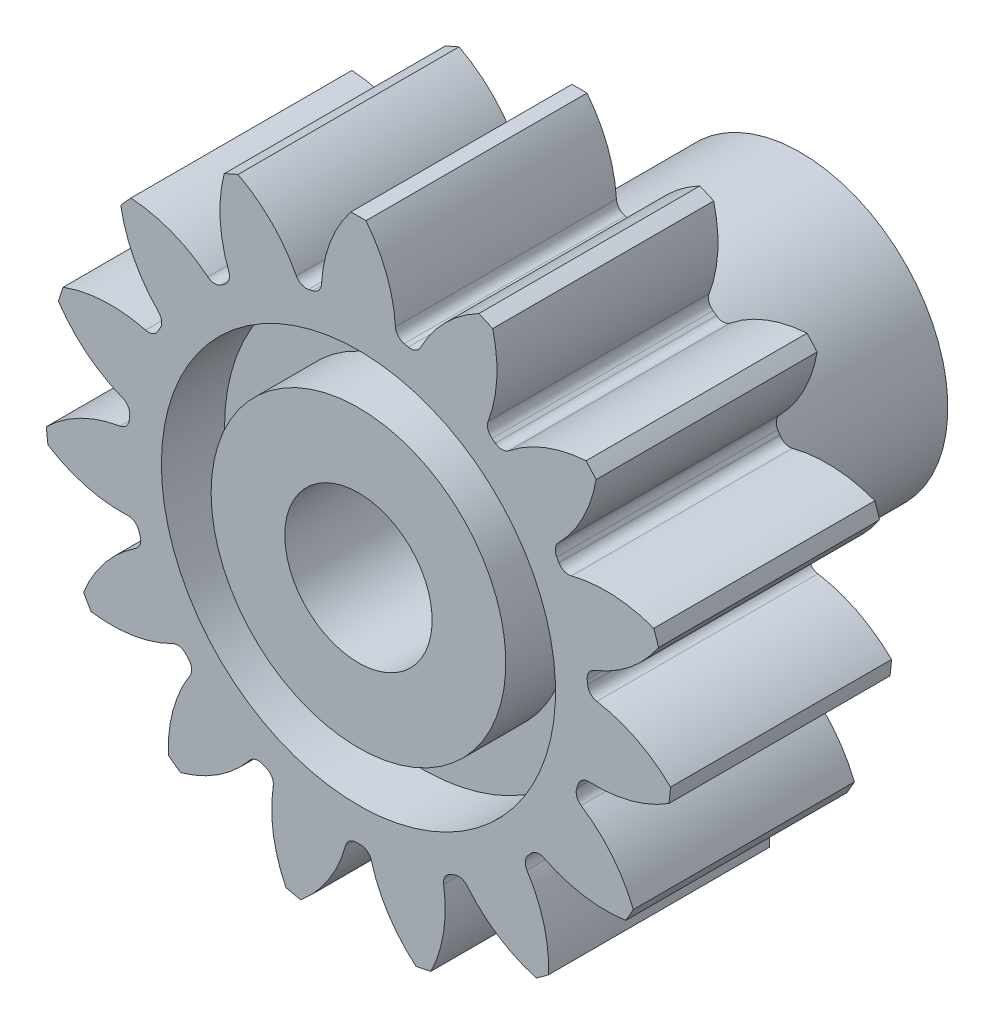
SolidWorks part; units mm, degrees
ref_plane "Front Plane" through (0, 0, 0) normal (0, 0, 1) x (1, 0, 0)
ref_plane "Top Plane" through (0, 0, 0) normal (0, 1, 0) x (1, 0, 0)
ref_plane "Right Plane" through (0, 0, 0) normal (1, 0, 0) x (0, 0, -1)
sketch "Sketch1" plane through (0, 0, 0) normal (1, 0, 0) x (0, 0, -1)
  line L0 (-6, 0) -> (-6, 8.5)
  line L1 (-6, 8.5) -> (0, 8.5)
  line L2 (0, 8.5) -> (0, 4)
  line L3 (0, 4) -> (6, 4)
  line L4 (6, 4) -> (6, 0)
  line L5 (6, 0) -> (-6, 0) construction
  line L6 (-6, 2) -> (6, 2)
  point P9 (-6, 5.35)
  dimension "OD" = 17
  dimension "Face Width" = 6
  dimension "Hub Width" = 6
  dimension "Hub Diameter" = 8
  dimension "For Shaft Diameter" = 4
  dimension "Overall Width" = 12
  dimension "Under Cut Diameter" = 10.7
sketch "Sketch2" plane through (0, 0, 0) normal (0, 0, 1) x (1, 0, 0)
  line L0 (-1.273, 6.119) -> (-0.4064, 8.5)
  line L1 (-0.4064, 8.5) -> (0.4064, 8.5)
  line L2 (0.4064, 8.5) -> (1.273, 6.119)
  line L3 (0, 8.5) -> (0, 0) construction
  line L4 (0, 0) -> (-1.7672, 8.3143) construction
  line L5 (0, 0) -> (1.7672, 8.3143) construction
  line L6 (-3.6518, 5.0722) -> (-3.8285, 7.5998)
  line L7 (-3.8285, 7.5998) -> (-3.086, 7.9304)
  line L8 (-3.086, 7.9304) -> (-1.3258, 6.1078)
  line L9 (-3.4573, 7.7651) -> (0, 0) construction
  line L11 (-0.4064, 8.5) -> (0, 8.5) construction
  line L12 (-0.7854, 7.4588) -> (0.7854, 7.4588) construction
  circle A0 centre (0, 0) radius 7.5 construction
  circle A2 centre (0, 0) radius 8.5
  circle A3 centre (0, 0) radius 6.25
  arc A5 (-0.2032, 8.5) -> (-1.0101, 6.1678) centre (2.7162, 6.1843) ccw
  arc A6 (1.0101, 6.1678) -> (0.2032, 8.5) centre (-2.7162, 6.1843) ccw
  arc A7 (-1.5859, 6.0454) -> (-3.2716, 7.8478) centre (-4.9967, 4.5449) ccw
  arc A8 (-0.7854, 7.4588) -> (0.7854, 7.4588) centre (0, 0) cw
  point P3 (0, 7.5)
  point P5 (3.0505, 6.8516)
  point P9 (5.5736, 5.0185)
  point P10 (7.1329, 2.3176)
  point P11 (7.4589, -0.784)
  point P12 (6.4952, -3.75)
  point P13 (4.4084, -6.0676)
  point P14 (1.5593, -7.3361)
  point P15 (-1.5593, -7.3361)
  point P16 (-4.4084, -6.0676)
  point P17 (-6.4952, -3.75)
  point P18 (-7.4589, -0.784)
  point P19 (-7.1329, 2.3176)
  point P20 (-5.5736, 5.0185)
  point P21 (-3.0505, 6.8516)
  point P31 (0, 0)
  dimension "Gear Pitch Diameter" = 15
  dimension "Pressure Angle" = 20
  dimension "Addendum" = 1
  dimension "Dedendum" = 1.25
  dimension "D1" = 24
  dimension "D2" = 1.5708
  dimension "Number of Teeth" = 15
sketch "Sketch3" plane through (0, 0, 0) normal (1, 0, 0) x (0, 0, -1)
  line L0 (-6, 8.5) -> (0, 8.5) construction
  line L1 (6, 4) -> (6, 0) construction
  line L2 (0, 4) -> (6, 4) construction
  line L3 (0, 8.5) -> (0, 4) construction
  line L4 (-6, 0) -> (-6, 8.5) construction
  line L5 (-6, 2) -> (6, 2) construction
  line L6 (-6, 8.5) -> (0, 8.5)
  line L7 (6, 4) -> (6, 2)
  line L8 (-6, 4) -> (-4.2857, 4)
  line L9 (0, 8.5) -> (0, 5.35)
  line L10 (-6, 2) -> (-6, 4)
  line L11 (-6, 2) -> (6, 2)
  line L12 (-6, 5.35) -> (-4.2857, 5.35)
  line L13 (-4.2857, 5.35) -> (-4.2857, 4)
  line L14 (0, 5.35) -> (-1.7143, 5.35)
  line L15 (-1.7143, 5.35) -> (-1.7143, 4)
  line L16 (-1.7143, 4) -> (6, 4)
  line L17 (-6, 5.35) -> (-6, 8.5)
  dimension "D1" = 1.7143
revolve "Revolve1" add sketch "Sketch3" angle 360 about L5
sketch "Sketch4" plane through (0, 0, 6) normal (0, 0, 1) x (1, 0, 0)
  arc A1 (-0.2032, 8.5) -> (-1.0101, 6.1678) centre (2.7162, 6.1843) ccw construction
  arc A2 (-1.5859, 6.0454) -> (-3.2716, 7.8478) centre (-4.9967, 4.5449) ccw construction
  arc A3 (-0.2052, 8.4975) -> (-1.0038, 6.4015) centre (2.7162, 6.1843) ccw
  arc A4 (-1.6867, 6.2564) -> (-3.2688, 7.8463) centre (-4.9967, 4.5449) ccw
  circle A5 centre (0, 0) radius 8.5 construction
  arc A6 (-0.2052, 8.4975) -> (-3.2688, 7.8463) centre (0, 0) ccw
  circle A7 centre (0, 0) radius 6.25 construction
  arc A8 (-1.2436, 6.125) -> (-1.3552, 6.1013) centre (0, 0) ccw
  arc A9 (-1.6867, 6.2564) -> (-1.3552, 6.1013) centre (-1.4203, 6.3942) ccw
  arc A10 (-1.2436, 6.125) -> (-1.0038, 6.4015) centre (-1.3033, 6.419) ccw
  dimension "D1" = 0.3
extrude "Cut-Extrude1" cut sketch "Sketch4" against normal through all both and the other way through all
pattern_circular "CirPattern1" count 15 over 360 about axis through (0, 0, 0) along (0, 0, 1) of "Cut-Extrude1"
equation "\"Dedendum@Sketch2\" = 1.25 /  ( \"Number of Teeth@Sketch2\" / \"Gear Pitch Diameter@Sketch2\" ) "
equation "\"D1@Sketch2\"=360/\"Number of Teeth@Sketch2\""
equation "\"D1@Sketch4\"=.3/(\"Number of Teeth@Sketch2\"/\"Gear Pitch Diameter@Sketch2\")"
equation "\"D1@CirPattern1\"=\"Number of Teeth@Sketch2\""
equation "\"D2@Sketch2\"=1.5708/(\"Number of Teeth@Sketch2\"/\"Gear Pitch Diameter@Sketch2\")"
equation "\"D1@Sketch3\"=\"Face Width@Sketch1\"/3.5"
